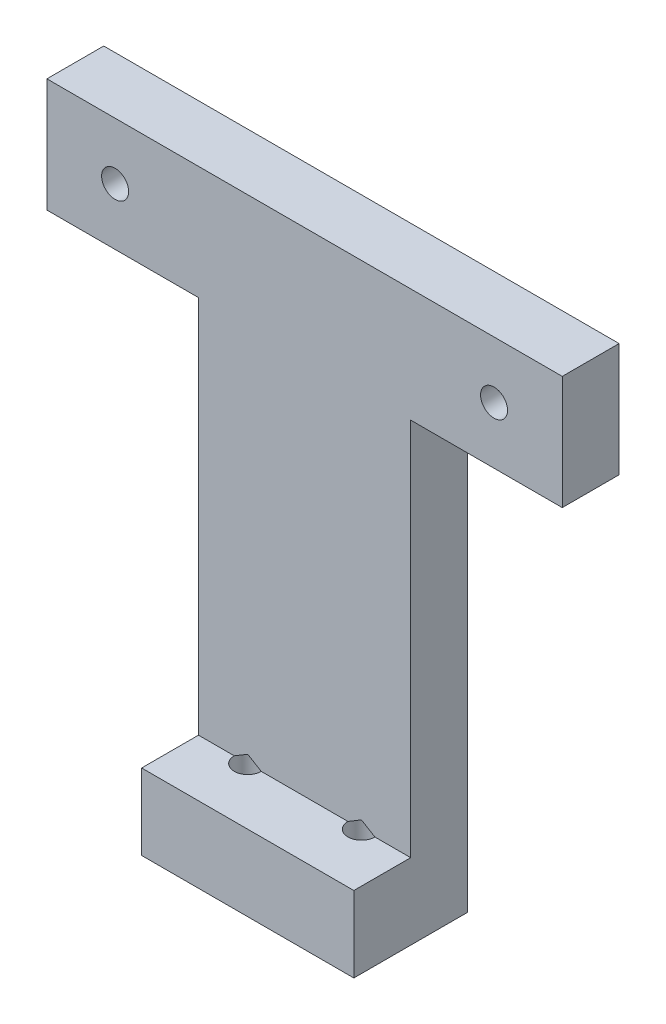
SolidWorks part; units mm, degrees
ref_plane "Front Plane" through (0, 0, 0) normal (0, 0, 1) x (1, 0, 0)
ref_plane "Top Plane" through (0, 0, 0) normal (0, 1, 0) x (1, 0, 0)
ref_plane "Right Plane" through (0, 0, 0) normal (1, 0, 0) x (0, 0, -1)
sketch "Sketch1" plane through (0, 0, 0) normal (0, 1, 0) x (1, 0, 0)
  line L1 (-8.89, -4.7625) -> (8.89, -4.7625)
  line L2 (-8.89, -4.7625) -> (-8.89, 4.7625)
  line L3 (-8.89, 4.7625) -> (8.89, 4.7625)
  line L4 (8.89, -4.7625) -> (8.89, 4.7625)
  line L5 (-8.89, -4.7625) -> (8.89, 4.7625) construction
  line L6 (-8.89, 4.7625) -> (8.89, -4.7625) construction
  point P0 (0, 0)
  dimension "D1" = 9.525
  dimension "D2" = 17.78
extrude "Boss-Extrude1" add sketch "Sketch1" along normal blind 47.625
sketch "Sketch2" plane through (0, 47.625, 0) normal (0, 1, 0) x (1, 0, 0)
  line L0 (8.89, -4.7625) -> (8.89, 4.7625) construction
  line L1 (-8.89, -4.7625) -> (8.89, -4.7625)
  line L2 (-8.89, -4.7625) -> (-8.89, 0)
  line L3 (-8.89, 0) -> (8.89, 0)
  line L4 (8.89, -4.7625) -> (8.89, 0)
  line L5 (8.89, 4.7625) -> (-8.89, 4.7625) construction
  dimension "D1" = 4.7625
extrude "Cut-Extrude1" cut sketch "Sketch2" against normal offset from surface (41.275 mm away) 6.35 up to face at (0, 0, 0)
hole_wizard "#4-40 Tapped Hole1" positions "Sketch4" profile "Sketch5" tap size "#4-40" standard "ANSI Inch"
sketch "Sketch4" plane through (0, 0, 0) normal (0, -1, 0) x (-1, 0, 0)
  line L4 (-4.7625, 0) -> (4.7625, 0) construction
  point P0 (-4.7625, 0)
  point P2 (4.7625, 0)
  dimension "D1" = 9.525
sketch "Sketch5" plane through (4.7625, 0, 0) normal (1, 0, 0) x (0, 0, -1)
  line L0 (0, 0) -> (0, 7.0292)
  line L1 (0, 7.0292) -> (1.1303, 6.35)
  line L2 (1.1303, 6.35) -> (1.1303, 0)
  line L5 (1.1303, 0) -> (0, 0)
  line L10 (0, 7.0292) -> (-1.1303, 6.35) construction
  line L11 (0, -6.35) -> (0, 107.95) construction
  dimension "Tap Drill Dia." = 2.2606
  dimension "Tap Drill Depth" = 6.35
  dimension "Drill Angle" = 118
cosmetic thread "Hole Thread1" parameters "D1"=5.588, "D2"=2.8448
cosmetic thread "Hole Thread2" parameters "D1"=5.588, "D2"=2.8448
sketch "Sketch9" plane through (-8.89, 0, 0) normal (-1, 0, 0) x (0, 0, 1)
  line L0 (0, 6.35) -> (0, 47.625) construction
  line L1 (-4.7625, 47.625) -> (0, 47.625)
  line L2 (-4.7625, 47.625) -> (-4.7625, 38.1)
  line L3 (-4.7625, 38.1) -> (0, 38.1)
  line L4 (0, 47.625) -> (0, 38.1)
  dimension "D1" = 9.525
extrude "Boss-Extrude2" add sketch "Sketch9" along normal blind 12.7
mirror "Mirror1" about plane through (0, 0, 0) normal (1, 0, 0) of "Boss-Extrude2"
sketch "Sketch10" plane through (0, 0, 0) normal (0, 0, 1) x (1, 0, 0)
  line L0 (-21.59, 42.8625) -> (21.59, 42.8625) construction
  line L3 (-21.59, 38.1) -> (-21.59, 47.625) construction
  line L4 (21.59, 38.1) -> (21.59, 47.625) construction
  circle A0 centre (-15.875, 42.8625) radius 1.1303
  circle A1 centre (15.875, 42.8625) radius 1.1303
  point P10 (0, 0)
  point P16 (0, 42.8625)
  dimension "D2" = 2.2606
  dimension "D3" = 2.2606
  dimension "D1" = 31.75
  dimension "D4" = 15.875
extrude "Cut-Extrude3" cut sketch "Sketch10" against normal through all
